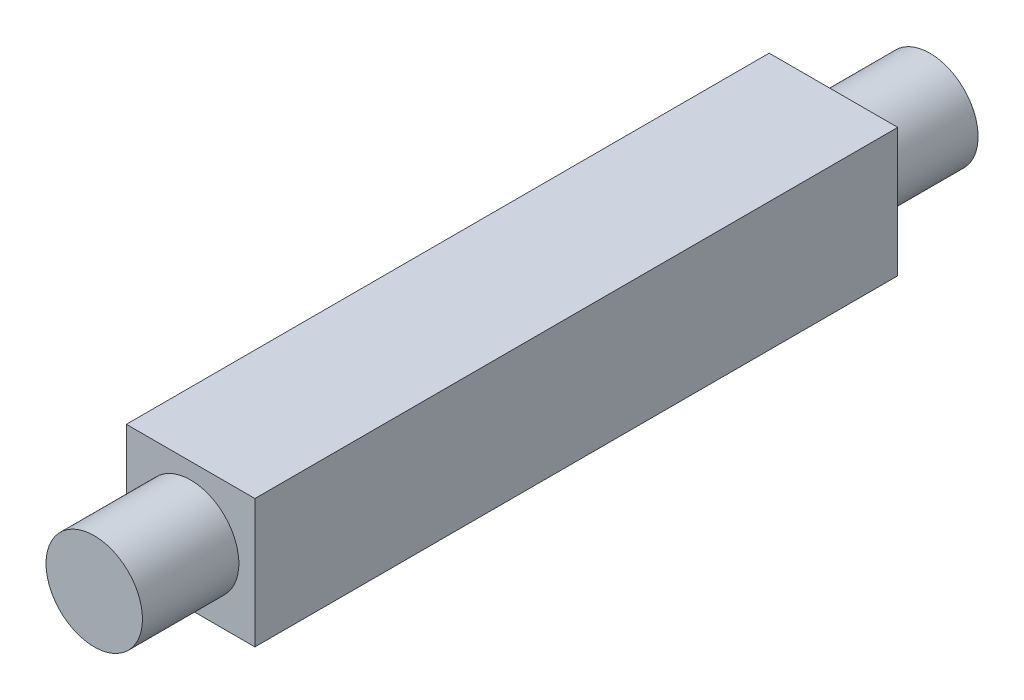
SolidWorks part; units mm, degrees
ref_plane "Front" through (0, 0, 0) normal (0, 0, 1) x (1, 0, 0)
ref_plane "Top" through (0, 0, 0) normal (0, 1, 0) x (1, 0, 0)
ref_plane "Right" through (0, 0, 0) normal (1, 0, 0) x (0, 0, -1)
sketch "Croquis1" plane through (0, 0, 0) normal (0, 0, 1) x (1, 0, 0)
  line L1 (-2, -2) -> (2, -2)
  line L2 (-2, -2) -> (-2, 2)
  line L3 (-2, 2) -> (2, 2)
  line L4 (2, -2) -> (2, 2)
  line L5 (-2, -2) -> (2, 2) construction
  line L6 (-2, 2) -> (2, -2) construction
  point P0 (0, 0)
  dimension "D1" = 4
  dimension "D2" = 4
extrude "Saliente-Extruir1" add sketch "Croquis1" along normal blind 20
sketch "Croquis2" plane through (0, 0, 0) normal (0, 0, -1) x (-1, 0, 0)
  circle A0 centre (0, 0) radius 1.5
  dimension "D1" = 3
extrude "Saliente-Extruir2" add sketch "Croquis2" along normal blind 3
ref_plane "Plano1" through (0, 0, 10) normal (0, 0, 1) x (1, 0, 0)
mirror "Simetría1" about plane through (0, 0, 10) normal (0, 0, 1) of "Saliente-Extruir2"
